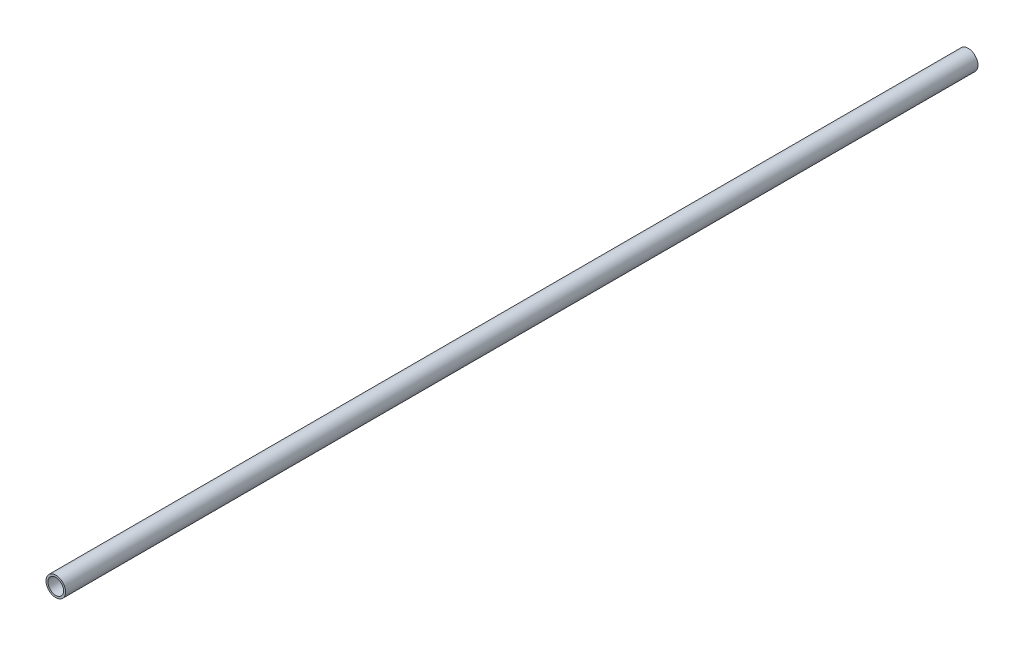
SolidWorks part; units mm, degrees
ref_plane "Front Plane" through (0, 0, 0) normal (0, 0, 1) x (1, 0, 0)
ref_plane "Top Plane" through (0, 0, 0) normal (0, 1, 0) x (1, 0, 0)
ref_plane "Right Plane" through (0, 0, 0) normal (1, 0, 0) x (0, 0, -1)
sketch "Sketch1" plane through (0, 0, 0) normal (0, 0, 1) x (1, 0, 0)
  circle A0 centre (0, 0) radius 15
  dimension "D1" = 30
extrude "Boss-Extrude1" add sketch "Sketch1" along normal blind 1400
sketch "Sketch2" plane through (0, 0, 0) normal (0, 0, 1) x (1, 0, 0)
  circle A0 centre (0, 0) radius 12
  dimension "D1" = 24
extrude "Cut-Extrude1" cut sketch "Sketch2" along normal blind 1400
